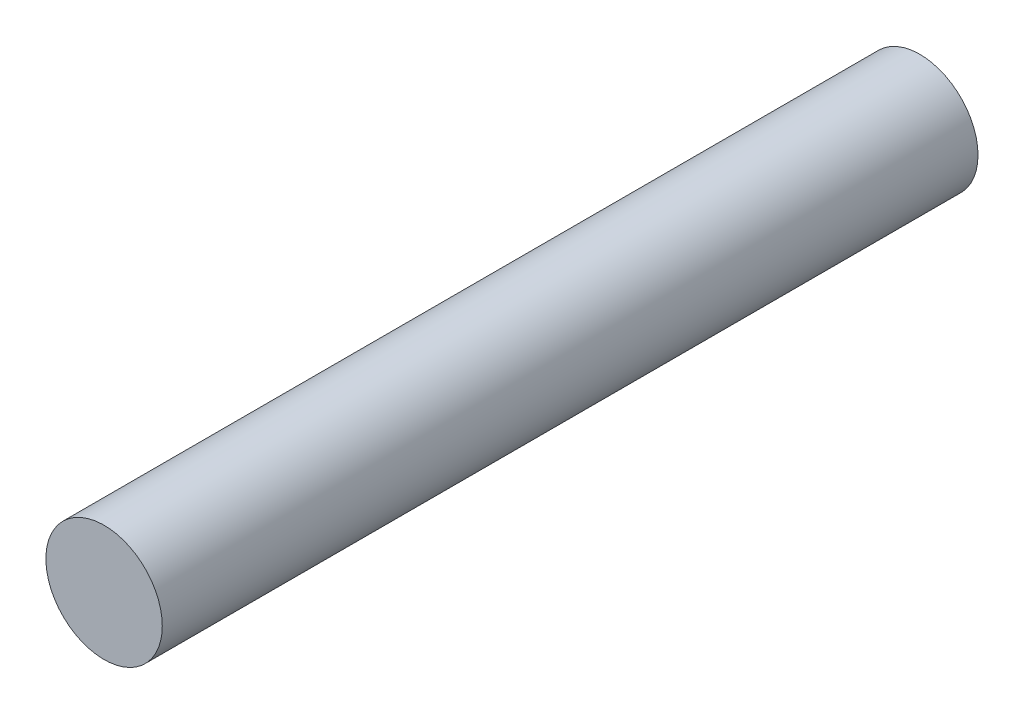
SolidWorks part; units mm, degrees
ref_plane "Front Plane" through (0, 0, 0) normal (0, 0, 1) x (1, 0, 0)
ref_plane "Top Plane" through (0, 0, 0) normal (0, 1, 0) x (1, 0, 0)
ref_plane "Right Plane" through (0, 0, 0) normal (1, 0, 0) x (0, 0, -1)
sketch "Sketch1" plane through (0, 0, 0) normal (0, 0, 1) x (1, 0, 0)
  circle A0 centre (0, 0) radius 14.478
  dimension "D1" = 28.956
extrude "Boss-Extrude1" add sketch "Sketch1" along normal blind 202.946
